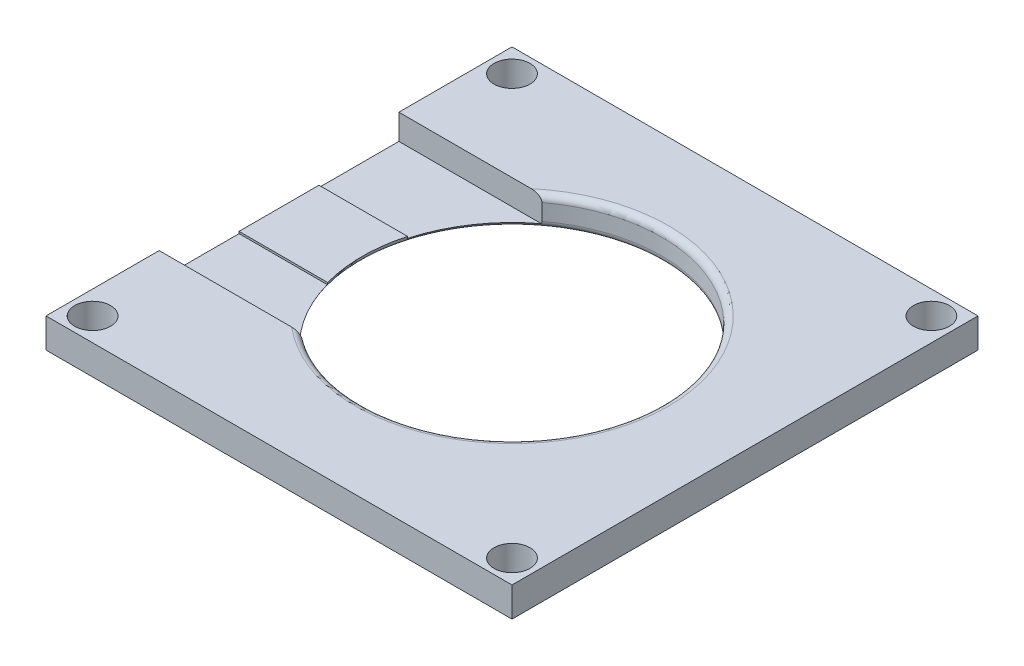
SolidWorks part; units mm, degrees
ref_plane "Front Plane" through (0, 0, 0) normal (0, 0, 1) x (1, 0, 0)
ref_plane "Top Plane" through (0, 0, 0) normal (0, 1, 0) x (1, 0, 0)
ref_plane "Right Plane" through (0, 0, 0) normal (1, 0, 0) x (0, 0, -1)
sketch "Sketch1" plane through (0, 0, 0) normal (0, 1, 0) x (1, 0, 0)
  line L0 (0, 35) -> (0, -35) construction
  line L1 (35, 35) -> (-35, 35)
  line L2 (35, 35) -> (35, -35)
  line L3 (35, -35) -> (-35, -35)
  line L4 (-35, 35) -> (-35, -35)
  line L5 (35, 35) -> (-35, -35) construction
  line L6 (35, -35) -> (-35, 35) construction
  line L7 (-35, 0) -> (35, 0) construction
  circle A0 centre (-31.5, 31.5) radius 2.7
  circle A1 centre (31.5, 31.5) radius 2.7
  circle A2 centre (31.5, -31.5) radius 2.7
  circle A3 centre (-31.5, -31.5) radius 2.7
  point P0 (0, 0)
  dimension "D3" = 5.4
  dimension "D1" = 70
  dimension "D2" = 70
  dimension "D4" = 3.5
  dimension "D5" = 3.5
extrude "Boss-Extrude1" add sketch "Sketch1" along normal blind 4.45 contours L1 L4 L3 L2 A1 A0 A2 A3
sketch "Sketch2" plane through (0, 4.45, 0) normal (0, 1, 0) x (1, 0, 0)
  circle A0 centre (0, 0) radius 22.5
  dimension "D1" = 45
extrude "Cut-Extrude1" cut sketch "Sketch2" against normal through all
fillet "Fillet1" radius 1 1 edges at (0, 4.45, 22.5)
sketch "Sketch4" plane through (0, 4.45, 0) normal (0, 1, 0) x (1, 0, 0)
  line L0 (-35, 35) -> (-35, -35) construction
  line L1 (-35, 6) -> (-25, 6)
  line L3 (-35, -6) -> (-25, -6)
  line L4 (-25, 6) -> (-25, -6)
  line L5 (-35, 0) -> (-25, -6) construction
  line L6 (-35, 0) -> (-25, 6) construction
  line L7 (-35, 6) -> (-35, -6)
  line L8 (35, 35) -> (-35, 35) construction
  line L10 (35, -35) -> (-35, -35) construction
  point P0 (-35, 0)
  dimension "D1" = 29
  dimension "D2" = 29
  dimension "D3" = 10
extrude "Cut-Extrude3" cut sketch "Sketch4" against normal blind 3.5
fillet "Fillet2" radius 1 1 edges at (0, 0, 22.5)
fillet "Fillet3" radius 1 2 edges at (-30, 4.45, 6) (-30, 4.45, -6)
sketch "Sketch6" plane through (-35, 0, 0) normal (-1, 0, 0) x (0, 0, 1)
  line L0 (7, 4.45) -> (18, 4.45)
  line L1 (7, 4.45) -> (35, 4.45) construction
  line L2 (18, 4.45) -> (18, 0.65)
  line L3 (18, 0.65) -> (6, 0.65)
  line L4 (6, 0.95) -> (6, 3.45) construction
  line L5 (6, 0.65) -> (6, 3.45)
  line L6 (0, 0) -> (0, 4.45) construction
  line L7 (7, 4.45) -> (-7, 4.45) construction
  line L8 (-7, 4.45) -> (-18, 4.45)
  line L9 (-18, 4.45) -> (-18, 0.65)
  line L10 (-18, 0.65) -> (-6, 0.65)
  line L11 (-6, 0.65) -> (-6, 3.45)
  arc A0 (7, 4.45) -> (6, 3.45) centre (7, 3.45) ccw construction
  arc A1 (7, 4.45) -> (6, 3.45) centre (7, 3.45) ccw
  arc A2 (-7, 4.45) -> (-6, 3.45) centre (-7, 3.45) cw
  dimension "D1" = 11
  dimension "D2" = 3.8
extrude "Cut-Extrude4" cut sketch "Sketch6" against normal blind 27.5
sketch "Sketch7" plane through (-25, 0, 0) normal (-1, 0, 0) x (0, 0, 1)
  line L6 (7, 4.45) -> (-7, 4.45)
  line L7 (-6, 3.45) -> (-6, 0.95)
  line L9 (-6, 0.95) -> (6, 0.95)
  line L11 (6, 0.95) -> (6, 3.45)
  line L12 (7, 4.45) -> (-7, 4.45)
  line L13 (-6, 3.45) -> (-6, 0.95)
  line L15 (-6, 0.95) -> (6, 0.95)
  line L17 (6, 0.95) -> (6, 3.45)
  arc A2 (-6, 3.45) -> (-7, 4.45) centre (-7, 3.45) ccw
  arc A3 (7, 4.45) -> (6, 3.45) centre (7, 3.45) ccw
  arc A4 (-6, 3.45) -> (-7, 4.45) centre (-7, 3.45) ccw
  arc A5 (7, 4.45) -> (6, 3.45) centre (7, 3.45) ccw
  dimension "D1" = 0
extrude "Cut-Extrude5" cut sketch "Sketch7" against normal blind 14.5
